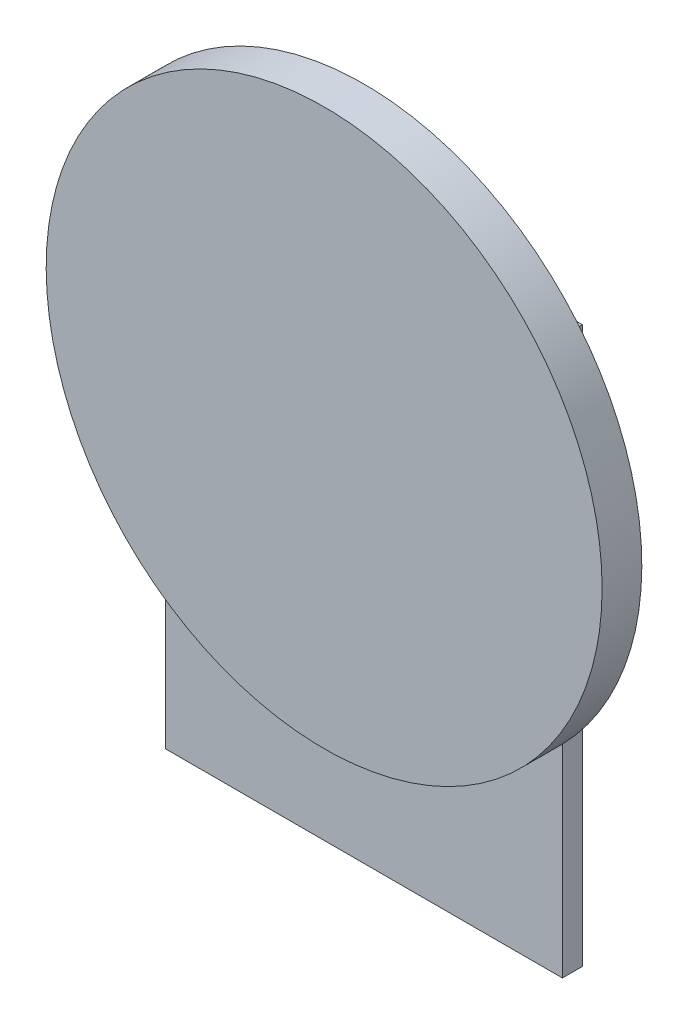
SolidWorks part; units mm, degrees
ref_plane "Front Plane" through (0, 0, 0) normal (0, 0, 1) x (1, 0, 0)
ref_plane "Top Plane" through (0, 0, 0) normal (0, 1, 0) x (1, 0, 0)
ref_plane "Right Plane" through (0, 0, 0) normal (1, 0, 0) x (0, 0, -1)
sketch "Sketch1" plane through (0, 0, 0) normal (0, 0, 1) x (1, 0, 0)
  circle A0 centre (0, 0) radius 7
  dimension "D1" = 14
extrude "Boss-Extrude1" add sketch "Sketch1" along normal blind 1
sketch "Sketch2" plane through (0, 0, 0) normal (0, 0, -1) x (-1, 0, 0)
  line L1 (-5, 4) -> (5, 4)
  line L2 (-5, 4) -> (-5, -10)
  line L3 (-5, -10) -> (5, -10)
  line L4 (5, 4) -> (5, -10)
  point P4 (0, 4)
  dimension "D1" = 10
  dimension "D2" = 14
  dimension "D3" = 4
extrude "Boss-Extrude2" add sketch "Sketch2" along normal blind 0.5
